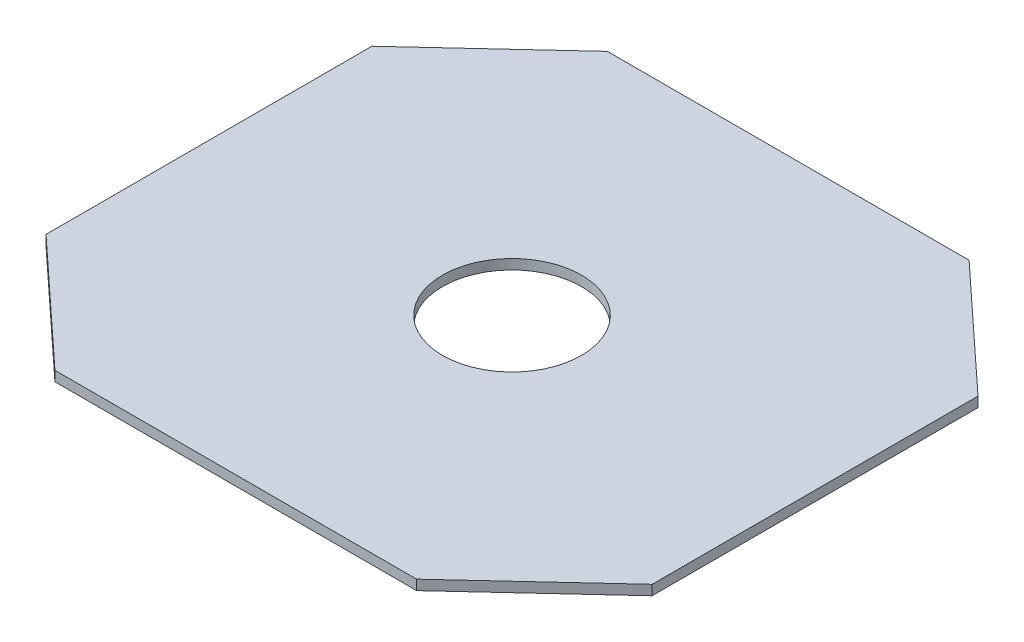
SolidWorks part; units mm, degrees
ref_plane "Спереди" through (0, 0, 0) normal (0, 0, 1) x (1, 0, 0)
ref_plane "Сверху" through (0, 0, 0) normal (0, 1, 0) x (1, 0, 0)
ref_plane "Справа" through (0, 0, 0) normal (1, 0, 0) x (0, 0, -1)
sketch "Эскиз1" plane through (0, 0, 0) normal (0, 1, 0) x (1, 0, 0)
  line L0 (-151.6931, 77.9165) -> (-151.6931, -86.0835)
  line L1 (-90.1931, 134.9165) -> (91.8069, 134.9165)
  line L2 (-151.6931, -4.0835) -> (385.0118, -4.0835) construction
  line L3 (-151.6931, 77.9165) -> (-90.1931, 134.9165)
  line L5 (-151.6931, -86.0835) -> (-90.1931, -143.0835)
  line L6 (153.3069, 77.9165) -> (91.8069, 134.9165)
  line L7 (153.3069, -86.0835) -> (91.8069, -143.0835)
  line L8 (-90.1931, -143.0835) -> (91.8069, -143.0835)
  line L9 (153.3069, 77.9165) -> (153.3069, -86.0835)
  line L10 (0.8069, -141.1933) -> (0.8069, -110.0578) construction
  circle A0 centre (0.8069, -4.0835) radius 35
  dimension "D1" = 139
  dimension "D5" = 91
  dimension "D4" = 91
  dimension "D2" = 139
  dimension "D3" = 82
  dimension "D6" = 91
  dimension "D7" = 91
  dimension "D8" = 82
  dimension "D9" = 82
  dimension "D10" = 82
extrude "Вытянуть1" add sketch "Эскиз1" along normal blind 5
